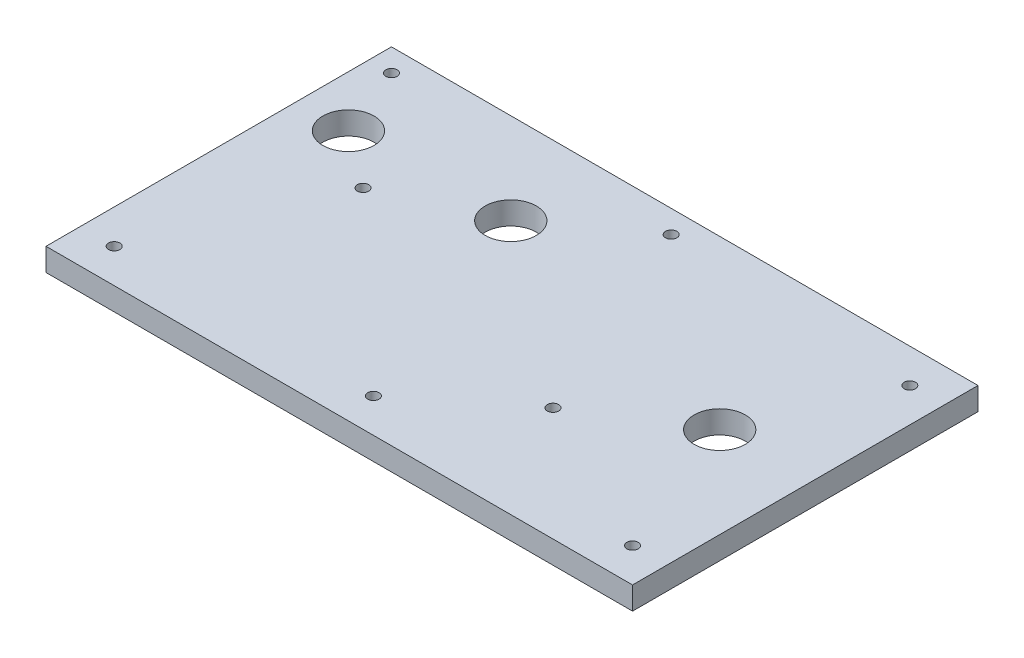
SolidWorks part; units mm, degrees
ref_plane "Front Plane" through (0, 0, 0) normal (0, 0, 1) x (1, 0, 0)
ref_plane "Top Plane" through (0, 0, 0) normal (0, 1, 0) x (1, 0, 0)
ref_plane "Right Plane" through (0, 0, 0) normal (1, 0, 0) x (0, 0, -1)
sketch "Sketch1" plane through (0, 0, 0) normal (0, 1, 0) x (1, 0, 0)
  line L0 (0, 0) -> (186.9461, 0) construction
  line L1 (0, 0) -> (159.4744, -42.731) construction
  line L2 (-30.2404, -112.8588) -> (-112.7308, -90.7556) construction
  line L3 (-112.7308, -90.7556) -> (-88.9, -1.8179) construction
  line L4 (0, -116.84) -> (159.4744, -116.84) construction
  line L5 (-117.475, 50.8) -> (210.2744, 50.8)
  line L6 (-117.475, 50.8) -> (-117.475, -142.24)
  line L7 (-117.475, -142.24) -> (210.2744, -142.24)
  line L8 (210.2744, 50.8) -> (210.2744, -142.24)
  circle A1 centre (159.4744, -42.731) radius 50.8 construction
  circle A2 centre (0, 0) radius 50.8 construction
  circle A3 centre (-88.9, -1.8179) radius 28.575 construction
  circle A4 centre (0, 0) radius 116.84 construction
  circle A5 centre (0, 0) radius 14.2875
  circle A6 centre (159.4744, -42.731) radius 14.2875
  circle A7 centre (-88.9, -1.8179) radius 14.2875
  circle A8 centre (-98.425, -123.19) radius 3.175
  circle A9 centre (191.2244, -123.19) radius 3.175
  circle A10 centre (191.2244, 31.75) radius 3.175
  circle A11 centre (102.3244, -78.74) radius 3.175
  circle A12 centre (46.3997, -123.19) radius 3.175
  circle A14 centre (-57.15, -25.4) radius 3.175
  circle A15 centre (-104.775, 38.1) radius 3.175
  circle A16 centre (51.5244, 38.1) radius 3.175
  dimension "D1" = 165.1
  dimension "D4" = 101.6
  dimension "D5" = 233.68
  dimension "D2" = 57.15
  dimension "D7" = 15
  dimension "D10" = 28.575
  dimension "D12" = 19.05
  dimension "D13" = 6.35
  dimension "D14" = 19.05
  dimension "D16" = 19.05
  dimension "D17" = 19.05
  dimension "D18" = 107.95
  dimension "D21" = 19.05
  dimension "D22" = 12.7
  dimension "D23" = 76.2
  dimension "D24" = 12.7
  dimension "D25" = 60.325
  dimension "D26" = 158.75
  dimension "D27" = 12.7
  dimension "D3" = 15
  dimension "D6" = 92.075
  dimension "D8" = 88.9
  dimension "D9" = 25.4
  dimension "D11" = 19.05
  dimension "D15" = 19.05
  dimension "D19" = 63.5
  dimension "D20" = 163.8747
extrude "Boss-Extrude1" add sketch "Sketch1" along normal blind 12.7
